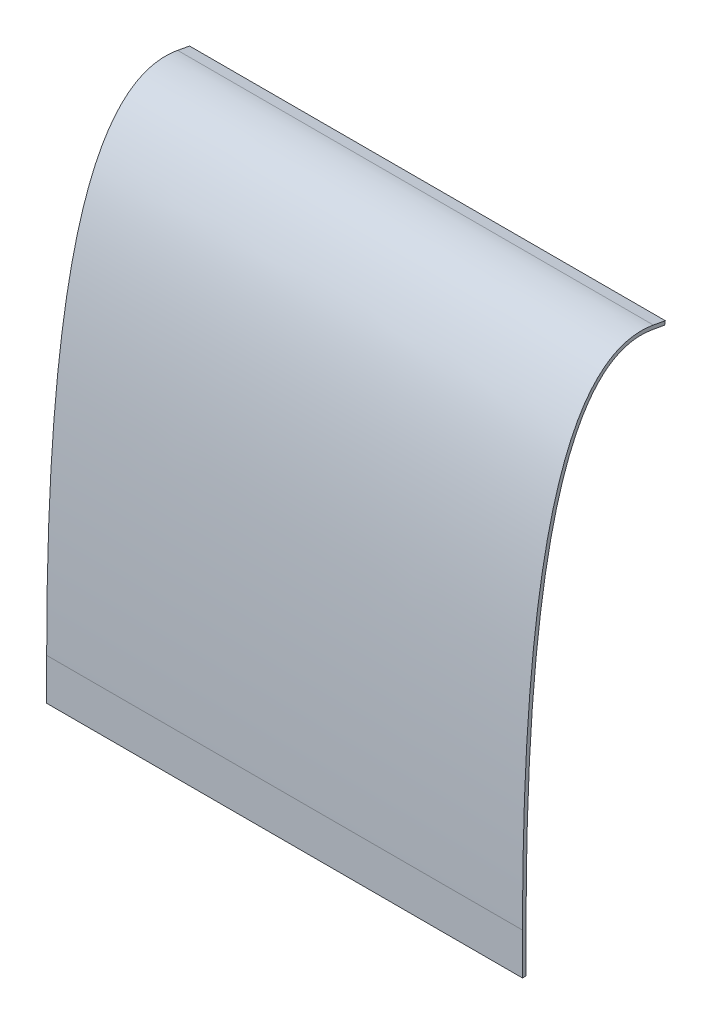
SolidWorks part; units mm, degrees
material "ABS"
ref_plane "Front Plane" through (0, 0, 0) normal (0, 0, 1) x (1, 0, 0)
ref_plane "Top Plane" through (0, 0, 0) normal (0, 1, 0) x (1, 0, 0)
ref_plane "Right Plane" through (0, 0, 0) normal (1, 0, 0) x (0, 0, -1)
sketch "Sketch1" plane through (0, 0, 0) normal (0, 0, 1) x (1, 0, 0)
  line L1 (0, -5389.8538) -> (418.0789, -5389.8538)
  line L2 (0, -5389.8538) -> (0, -5353.3689)
  line L3 (0, -5353.3689) -> (418.0789, -5353.3689)
  line L4 (418.0789, -5389.8538) -> (418.0789, -5353.3689)
extrude "Boss-Extrude1" add sketch "Sketch1" along normal blind 3.175
sketch "Sketch7" plane through (0, 0, 0) normal (-1, 0, 0) x (0, 0, 1)
  line L0 (-111.3306, -4953.6212) -> (-121.7981, -4955.5387) construction
  line L1 (-111.3306, -4953.6212) -> (-121.7981, -4955.5387)
  line L2 (-111.9027, -4950.4981) -> (-122.3702, -4952.4157)
  line L3 (0, -5353.3689) -> (3.175, -5353.3689)
  line L4 (-121.7981, -4955.5387) -> (-122.3702, -4952.4157)
  parabola Q1 (0, -5353.3689) -> (-111.3306, -4953.6212) focus (-95.1822, -4976.731) apex (-89.4683, -4954.121) construction
  parabola Q2 (0, -5353.3689) -> (-111.3306, -4953.6212) focus (-95.1822, -4976.731) apex (-89.4683, -4954.121)
  spline S0 degree 1 poles (3.175, -5353.3689) (-111.9027, -4950.4981) knots 0 0 1 1 construction
  spline S1 degree 3 poles (3.175, -5353.3689) (3.175, -5351.1874) (3.1705, -5346.8114) (3.1433, -5338.1634) (3.0752, -5327.4764) (2.9392, -5314.8715) (2.6852, -5298.3493) (2.2316, -5278.2336) (1.4695, -5254.9527) (0.4894, -5232.5297) (-1.108, -5203.7757) (-3.6502, -5169.9763) (-7.5749, -5132.8427) (-12.3759, -5099.1302) (-18.0569, -5068.8329) (-26.8143, -5032.9794) (-37.3605, -5003.9187) (-49.7958, -4981.5989) (-60.1213, -4968.2274) (-71.513, -4958.2588) (-81.9237, -4952.8809) (-90.7534, -4950.4066) (-97.598, -4949.4717) (-103.4746, -4949.4595) (-108.2539, -4949.9016) (-110.6968, -4950.2772) (-111.9027, -4950.4981) knots 0.490445 0.490445 0.490445 0.490445 0.490529 0.490612 0.490779 0.490945 0.491112 0.491445 0.491778 0.492111 0.492444 0.49311 0.493776 0.494442 0.495108 0.495775 0.497107 0.497773 0.498439 0.499105 0.499771 0.500104 0.500437 0.500771 0.500937 0.501104 0.501104 0.501104 0.501104
  dimension "D1" = 3.175
sweep "Sweep1" add profiles "Sketch7" path edge at (209.0395, -5353.3689, 0)
